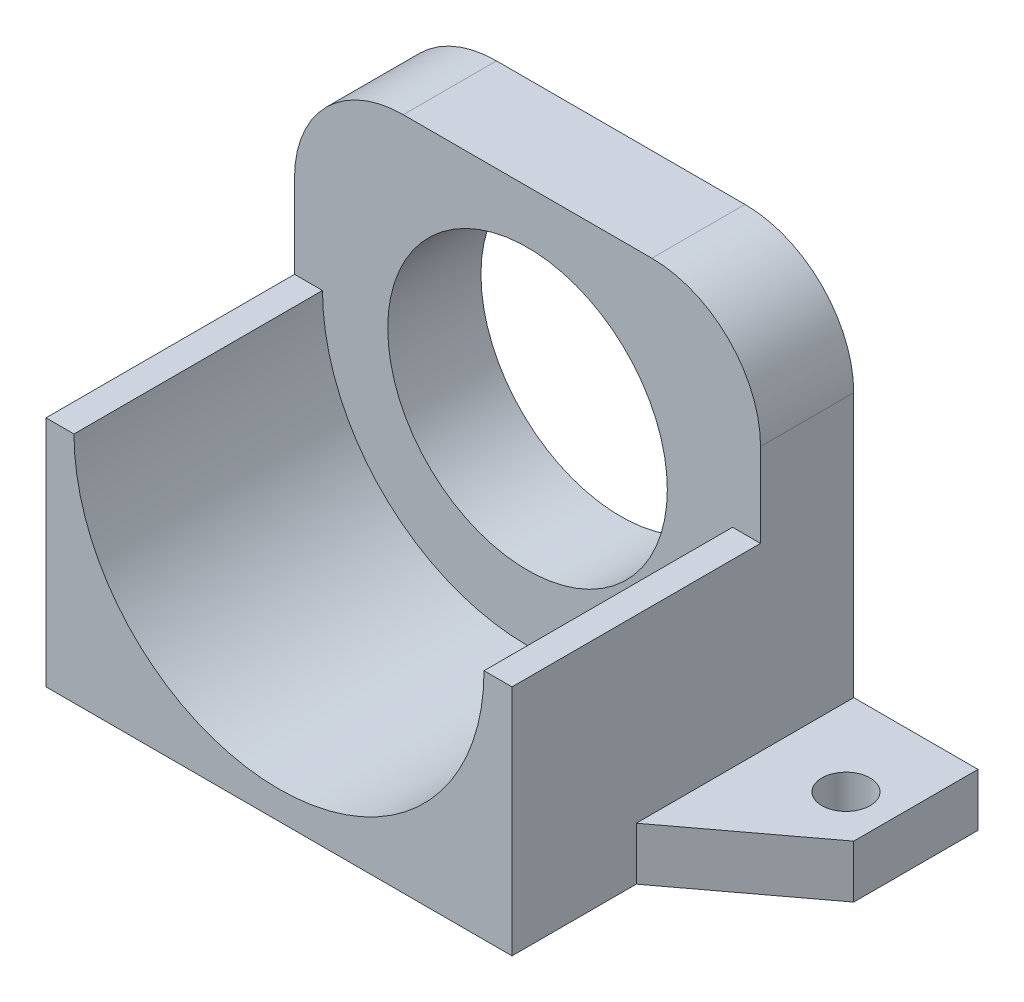
SolidWorks part; units mm, degrees
ref_plane "Front Plane" through (0, 0, 0) normal (0, 0, 1) x (1, 0, 0)
ref_plane "Top Plane" through (0, 0, 0) normal (0, 1, 0) x (1, 0, 0)
ref_plane "Right Plane" through (0, 0, 0) normal (1, 0, 0) x (0, 0, -1)
sketch "Sketch1" plane through (0, 0, 0) normal (0, 0, 1) x (1, 0, 0)
  line L0 (-23, 0) -> (23, 0)
  line L1 (23, 0) -> (23, 3.4)
  line L2 (23, 3.4) -> (15, 3.4)
  line L3 (-23, 0) -> (-23, 3.4)
  line L4 (-23, 3.4) -> (-15, 3.4)
  line L5 (-15, 3.4) -> (-15, 27.4)
  line L6 (-15, 27.4) -> (15, 27.4)
  line L7 (0, -22.1645) -> (0, 27.4) construction
  line L8 (15, 27.4) -> (15, 3.4)
  point P8 (0, 27.4)
  point P14 (0, 0)
  dimension "D1" = 46
  dimension "D2" = 3.4
  dimension "D3" = 30
  dimension "D4" = 24
extrude "Boss-Extrude1" add sketch "Sketch1" along normal blind 6
sketch "Sketch2" plane through (0, 0, 0) normal (0, 0, -1) x (-1, 0, 0)
  line L0 (23, 0) -> (-23, 0) construction
  circle A0 centre (0, 15) radius 9
  dimension "D1" = 18
  dimension "D2" = 15
extrude "Cut-Extrude1" cut sketch "Sketch2" against normal up to surface (6 mm away) up to face at (0, 8.55, 6)
fillet "Fillet1" radius 7 2 edges at (-15, 27.4, 3) (15, 27.4, 3)
sketch "Sketch4" plane through (0, 0, 6) normal (0, 0, 1) x (1, 0, 0)
  line L0 (-15, 0) -> (15, 0)
  line L1 (-23, 0) -> (23, 0) construction
  line L4 (-15, 20.4) -> (-15, 3.4) construction
  line L5 (15, 3.4) -> (15, 20.4) construction
  line L6 (-15, 0) -> (-15, 15)
  line L7 (-15, 15) -> (-13.2, 15)
  line L8 (15, 0) -> (15, 15)
  line L9 (15, 15) -> (13.2, 15)
  arc A0 (-13.2, 15) -> (13.2, 15) centre (0, 15) ccw
  dimension "D1" = 26.4
  dimension "D2" = 30
extrude "Boss-Extrude2" add sketch "Sketch4" along normal blind 16
sketch "Sketch5" plane through (0, 0, 6) normal (0, 0, 1) x (1, 0, 0)
  line L0 (-23, 3.4) -> (-23, 0)
  line L1 (-23, 0) -> (-15, 0)
  line L2 (-15, 0) -> (-15, 3.4)
  line L3 (-15, 3.4) -> (-23, 3.4)
  line L4 (23, 3.4) -> (23, 0)
  line L5 (23, 0) -> (15, 0)
  line L6 (15, 0) -> (15, 3.4)
  line L7 (15, 3.4) -> (23, 3.4)
extrude "Boss-Extrude3" add sketch "Sketch5" along normal blind 2
sketch "Sketch6" plane through (0, 3.4, 0) normal (0, 1, 0) x (1, 0, 0)
  line L0 (-15, -8) -> (-23, -8) construction
  circle A0 centre (20, -5.5) radius 1.55
  circle A1 centre (-20, -5.5) radius 1.55
  dimension "D2" = 3.1
  dimension "D3" = 3.1
  dimension "D5" = 2.5
  dimension "D1" = 40
  dimension "D4" = 20
extrude "Cut-Extrude3" cut sketch "Sketch6" against normal through all
sketch "Sketch8" plane through (0, 0, 0) normal (0, 1, 0) x (1, 0, 0)
  line L0 (-23, -8) -> (-15, -14)
  line L1 (-15, -22) -> (-15, -6) construction
  line L2 (-15, -14) -> (-15, -8)
  line L3 (-15, -8) -> (-23, -8)
  line L4 (15, -14) -> (23, -8)
  line L5 (15, -22) -> (15, -6) construction
  line L6 (23, -8) -> (15, -8)
  line L7 (15, -8) -> (15, -14)
extrude "Boss-Extrude5" add sketch "Sketch8" along normal up to surface (3.4 mm away) up to face at (-20, 3.4, 7.05)
